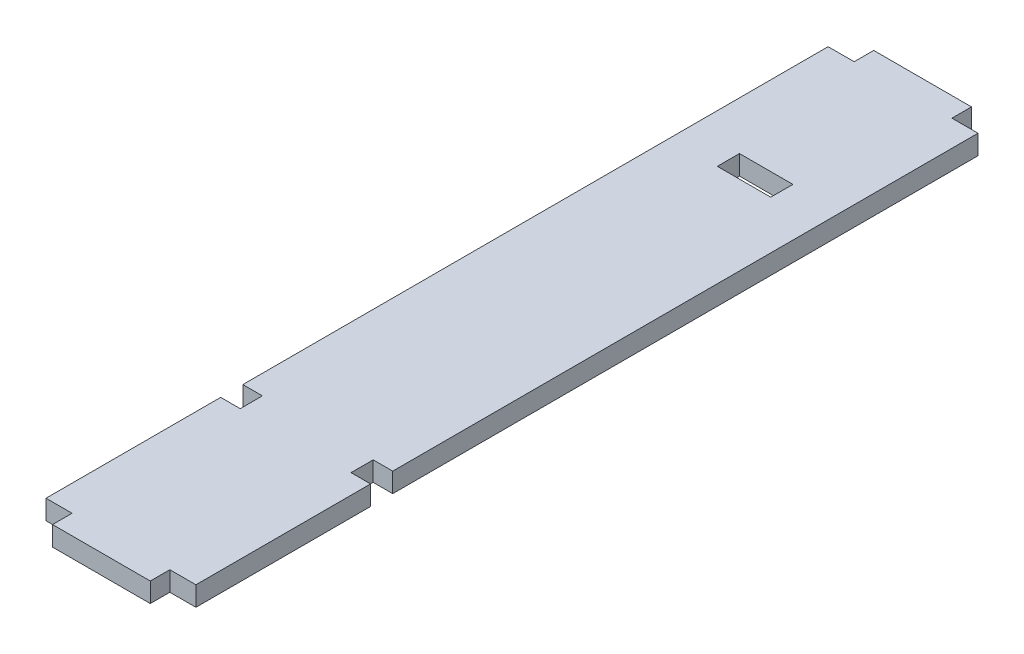
SolidWorks part; units mm, degrees
material "AISI 304"
ref_plane "Front Plane" through (0, 0, 0) normal (0, 0, 1) x (1, 0, 0)
ref_plane "Top Plane" through (0, 0, 0) normal (0, 1, 0) x (1, 0, 0)
ref_plane "Right Plane" through (0, 0, 0) normal (1, 0, 0) x (0, 0, -1)
sketch "Sketch1" plane through (0, 0, 0) normal (0, 1, 0) x (1, 0, 0)
  line L0 (3.75, 30) -> (5.75, 30)
  line L1 (-5.75, -30) -> (-3.75, -30)
  line L2 (-5.75, -30) -> (-5.75, -16.6)
  line L3 (-5.75, 30) -> (-3.75, 30)
  line L4 (5.75, -30) -> (5.75, -16.6)
  line L5 (-5.75, -30) -> (5.75, 30) construction
  line L6 (-5.75, 30) -> (5.75, -30) construction
  line L8 (3.75, 30) -> (3.75, 31.5)
  line L9 (3.75, 31.5) -> (-3.75, 31.5)
  line L10 (-3.75, 30) -> (-3.75, 31.5)
  line L12 (-3.75, -30) -> (-3.75, -31.5)
  line L13 (-3.75, -31.5) -> (3.75, -31.5)
  line L14 (3.75, -30) -> (3.75, -31.5)
  line L15 (3.75, -30) -> (5.75, -30)
  line L16 (-5.75, -14.9) -> (-5.75, 30)
  line L17 (-5.75, -14.9) -> (-4.25, -14.9)
  line L19 (-5.75, -16.6) -> (-4.25, -16.6)
  line L20 (-4.25, -14.9) -> (-4.25, -16.6)
  line L21 (5.75, -14.9) -> (5.75, 30)
  line L22 (5.75, -16.6) -> (4.25, -16.6)
  line L24 (5.75, -14.9) -> (4.25, -14.9)
  line L25 (4.25, -16.6) -> (4.25, -14.9)
  line L26 (0, 0) -> (0, 53.4412) construction
  line L32 (-2.05, 17.8) -> (2.05, 17.8)
  line L33 (-2.05, 17.8) -> (-2.05, 19.5)
  line L34 (-2.05, 19.5) -> (2.05, 19.5)
  line L35 (2.05, 17.8) -> (2.05, 19.5)
  line L36 (-2.05, 17.8) -> (2.05, 19.5) construction
  line L37 (-2.05, 19.5) -> (2.05, 17.8) construction
  point P0 (0, 0)
  point P22 (0, -31.5)
  point P23 (0, 18.65)
  dimension "D1" = 7.5
  dimension "D2" = 2
  dimension "D3" = 2
  dimension "D4" = 1.5
  dimension "D5" = 2
  dimension "D6" = 2
  dimension "D7" = 1.5
  dimension "D8" = 60
  dimension "D9" = 8.5
  dimension "D10" = 4.25
  dimension "D11" = 1.7
  dimension "D12" = 3.7
  dimension "D13" = 12
extrude "Boss-Extrude1" add sketch "Sketch1" along normal blind 1.5
